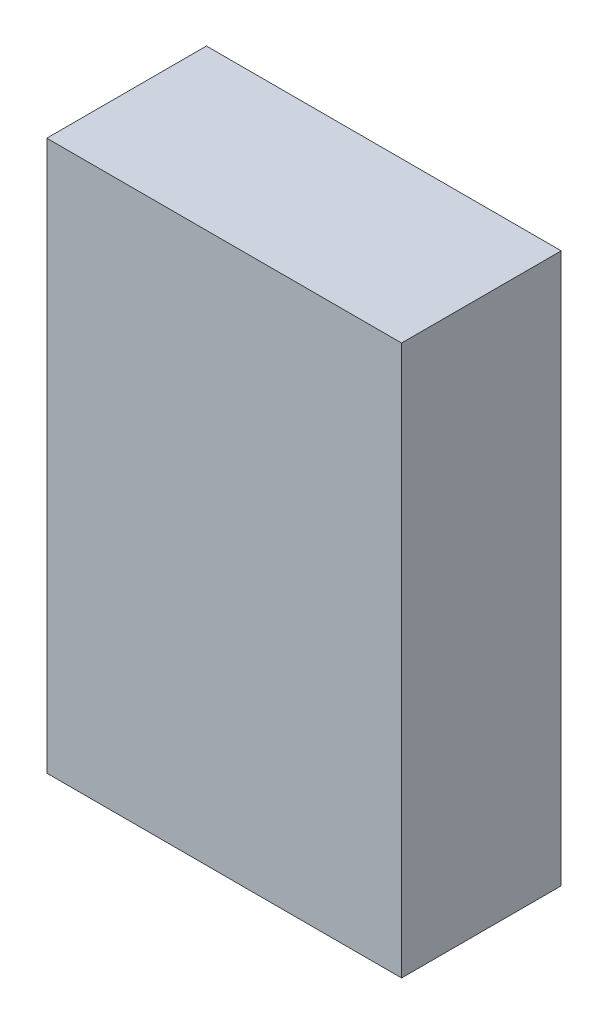
SolidWorks part; units mm, degrees
ref_plane "Plan de face" through (0, 0, 0) normal (0, 0, 1) x (1, 0, 0)
ref_plane "Plan de dessus" through (0, 0, 0) normal (0, 1, 0) x (1, 0, 0)
ref_plane "Plan de droite" through (0, 0, 0) normal (1, 0, 0) x (0, 0, -1)
sketch "Esquisse1" plane through (0, 0, 0) normal (0, 0, 1) x (1, 0, 0)
  line L1 (-28.0821, 37.0905) -> (-8.0821, 37.0905)
  line L2 (-28.0821, 37.0905) -> (-28.0821, 6.0905)
  line L3 (-28.0821, 6.0905) -> (-8.0821, 6.0905)
  line L4 (-8.0821, 37.0905) -> (-8.0821, 6.0905)
  dimension "D1" = 20
  dimension "D2" = 31
extrude "Extrusion1" add sketch "Esquisse1" along normal blind 9
